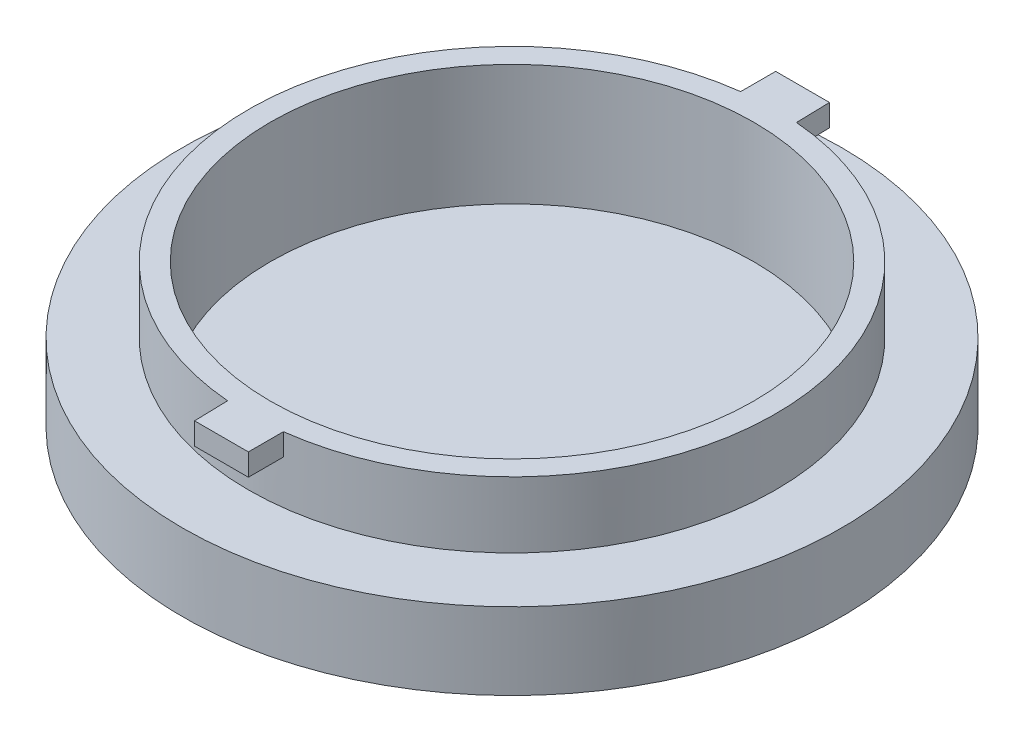
SolidWorks part; units mm, degrees
ref_plane "Front Plane" through (0, 0, 0) normal (0, 0, 1) x (1, 0, 0)
ref_plane "Top Plane" through (0, 0, 0) normal (0, 1, 0) x (1, 0, 0)
ref_plane "Right Plane" through (0, 0, 0) normal (1, 0, 0) x (0, 0, -1)
sketch "Sketch1" plane through (0, 0, 0) normal (0, 1, 0) x (1, 0, 0)
  circle A0 centre (0, 0) radius 30
extrude "Boss-Extrude1" add sketch "Sketch1" along normal blind 10
sketch "Sketch4" plane through (0, 10, 0) normal (0, 1, 0) x (1, 0, 0)
  circle A0 centre (0, 0) radius 24
extrude "Boss-Extrude2" add sketch "Sketch4" along normal blind 6
sketch "Sketch5" plane through (0, 16, 0) normal (0, 1, 0) x (1, 0, 0)
  circle A0 centre (0, 0) radius 22
extrude "Cut-Extrude2" cut sketch "Sketch5" against normal blind 11
sketch "Sketch8" plane through (0, 5, 0) normal (0, 1, 0) x (1, 0, 0)
  circle A0 centre (0, 0) radius 2
sketch "Sketch9" plane through (0, 16, 0) normal (0, 1, 0) x (1, 0, 0)
  line L1 (0.5, -23) -> (-2, -23)
  line L9 (0.5, -23) -> (3, -23)
  line L10 (3, -23) -> (3, -27)
  line L11 (-1.9008, -27) -> (3, -27)
  line L12 (-2, -23) -> (-1.9008, -27)
  line L13 (-3, 23) -> (-3, 27)
  line L14 (1.9008, 27) -> (-3, 27)
  line L15 (2, 23) -> (1.9008, 27)
  line L16 (-0.5, 23) -> (2, 23)
  line L17 (-0.5, 23) -> (-3, 23)
  point P13 (0, -0.712)
  point P14 (0, 0)
  dimension "D1" = 2
  dimension "D2" = 2.5
  dimension "D3" = 2.5
  dimension "D4" = 4
extrude "Boss-Extrude5" add sketch "Sketch9" against normal blind 2
sketch "Sketch10" plane through (0, 0, 0) normal (0, -1, 0) x (1, 0, 0)
  circle A0 centre (0, 0) radius 30
extrude "Cut-Extrude3" cut sketch "Sketch10" against normal blind 3
